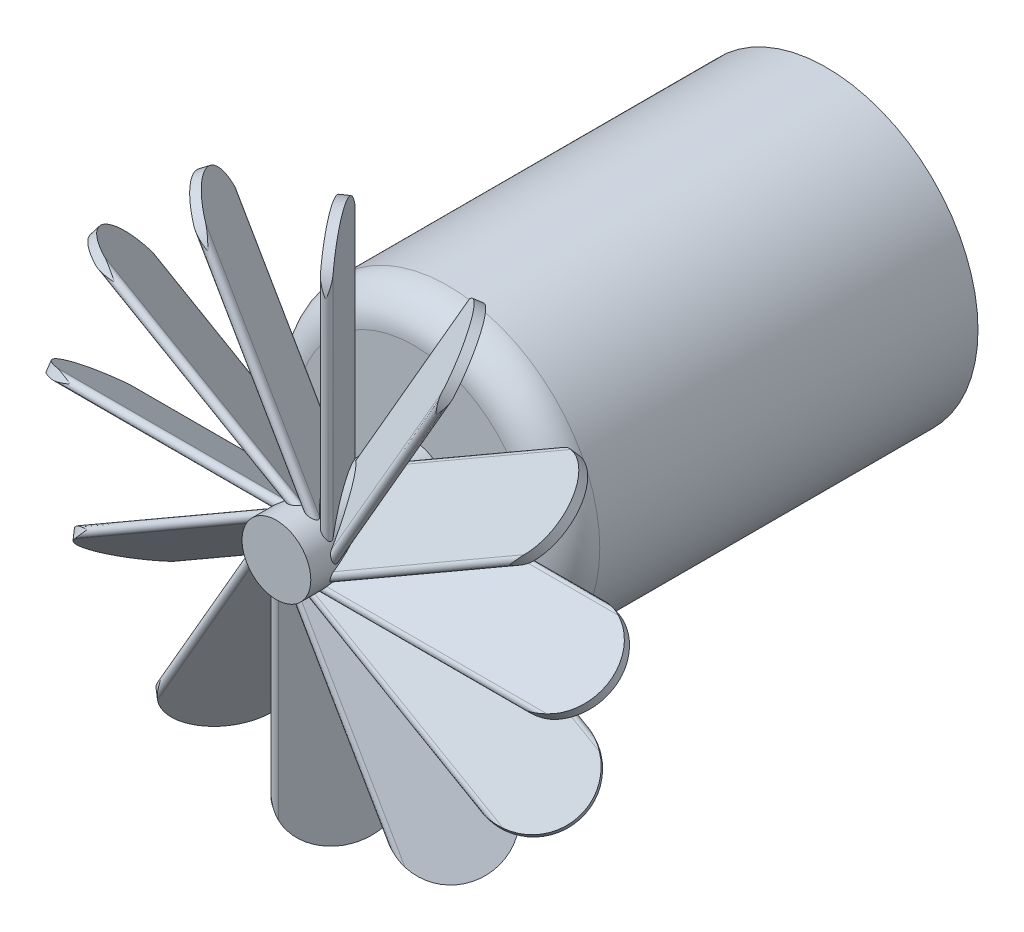
SolidWorks part; units mm, degrees
ref_plane "Front Plane" through (0, 0, 0) normal (0, 0, 1) x (1, 0, 0)
ref_plane "Top Plane" through (0, 0, 0) normal (0, 1, 0) x (1, 0, 0)
ref_plane "Right Plane" through (0, 0, 0) normal (1, 0, 0) x (0, 0, -1)
sketch "Sketch1" plane through (0, 0, 210) normal (0, 0, 1) x (1, 0, 0)
  circle A0 centre (750, 0) radius 44.0464
extrude "Boss-Extrude1" add sketch "Sketch1" along normal blind 120
fillet "Fillet1" radius 10 1 edges at (794.0464, 0, 330)
sketch "Sketch2" plane through (0, 0, 330) normal (0, 0, 1) x (1, 0, 0)
  circle A0 centre (750, 0) radius 10
  dimension "D1" = 20
extrude "Boss-Extrude2" add sketch "Sketch2" along normal blind 40
ref_point "Point1"
ref_plane "Plane1" through (0, 0, 0) normal (0, 1, 0) x (1, 0, 0)
sketch "Sketch3" plane through (0, 0, 0) normal (0, 1, 0) x (1, 0, 0)
  line L0 (742.7704, -341.7723) -> (757.2022, -362.5542) construction
  line L1 (743.8522, -341.0211) -> (758.284, -361.8029)
  line L2 (741.6885, -342.5236) -> (756.1204, -363.3054)
  arc A0 (743.8522, -341.0211) -> (741.6885, -342.5236) centre (742.7704, -341.7723) ccw
  arc A1 (756.1204, -363.3054) -> (758.284, -361.8029) centre (757.2022, -362.5542) ccw
  point P2 (749.9863, -352.1632)
extrude "Boss-Extrude3" add sketch "Sketch3" along normal blind 80
sketch "Sketch4" plane through (339.9048, 0, -236.045) normal (-0.8214, 0, 0.5704) x (0.5704, 0, 0.8214)
  line L0 (703.0775, 80) -> (703.0775, 6.0254) construction
  line L1 (731.0131, 6.0616) -> (731.0131, 80) construction
  line L2 (703.0692, 66.0239) -> (692.1279, 86.3093)
  line L3 (692.1279, 86.3093) -> (744.7451, 86.3093)
  line L4 (744.7451, 86.3093) -> (731.0131, 65.5424)
  arc A0 (703.0775, 65.5424) -> (731.0131, 65.5424) centre (717.0453, 66.0239) cw
  line M1 (704.3946, 80) -> (704.3946, 5.5605)
  line M3 (729.696, 7.9083) -> (729.696, 80)
  line M4 (729.696, 80) -> (704.3946, 80)
extrude "Cut-Extrude1" cut sketch "Sketch4" against normal blind 10 contours A0 M1 M4 | A0 M4 M3 | L2 A0 L4 L3 M1 M4 M3
pattern_circular "CirPattern1" count 12 over 360 about axis through (750, 0, 0) along (0, 0, 1) of "Boss-Extrude3", "Cut-Extrude1"
